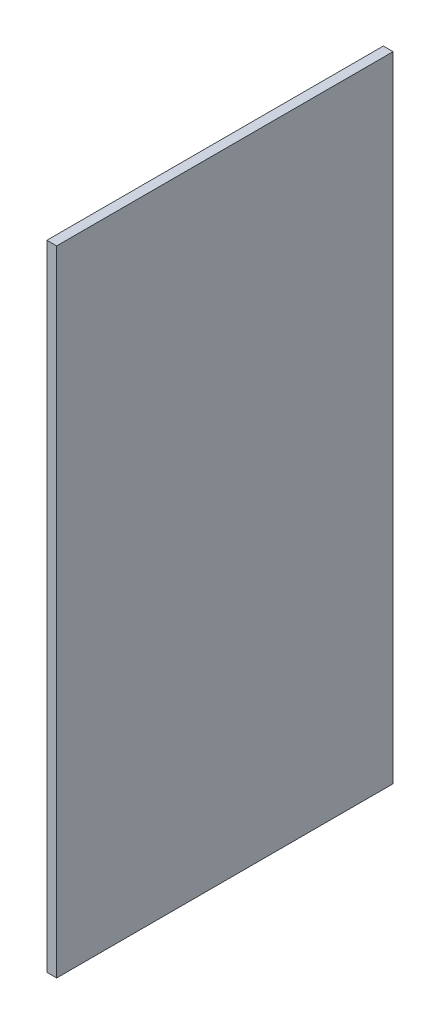
SolidWorks part; units mm, degrees
ref_plane "Front Plane" through (0, 0, 0) normal (0, 0, 1) x (1, 0, 0)
ref_plane "Top Plane" through (0, 0, 0) normal (0, 1, 0) x (1, 0, 0)
ref_plane "Right Plane" through (0, 0, 0) normal (1, 0, 0) x (0, 0, -1)
other "Configuration Table"
sketch "Sketch1" plane through (0, 0, 0) normal (0, 0, 1) x (1, 0, 0)
  line L1 (691, 182.5) -> (713, 182.5)
  line L2 (691, 182.5) -> (691, 1610)
  line L3 (691, 1610) -> (713, 1610)
  line L4 (713, 182.5) -> (713, 1610)
extrude "STORE_orta_bolme_pu_1" add sketch "Sketch1" against normal blind 757.5 separate body
